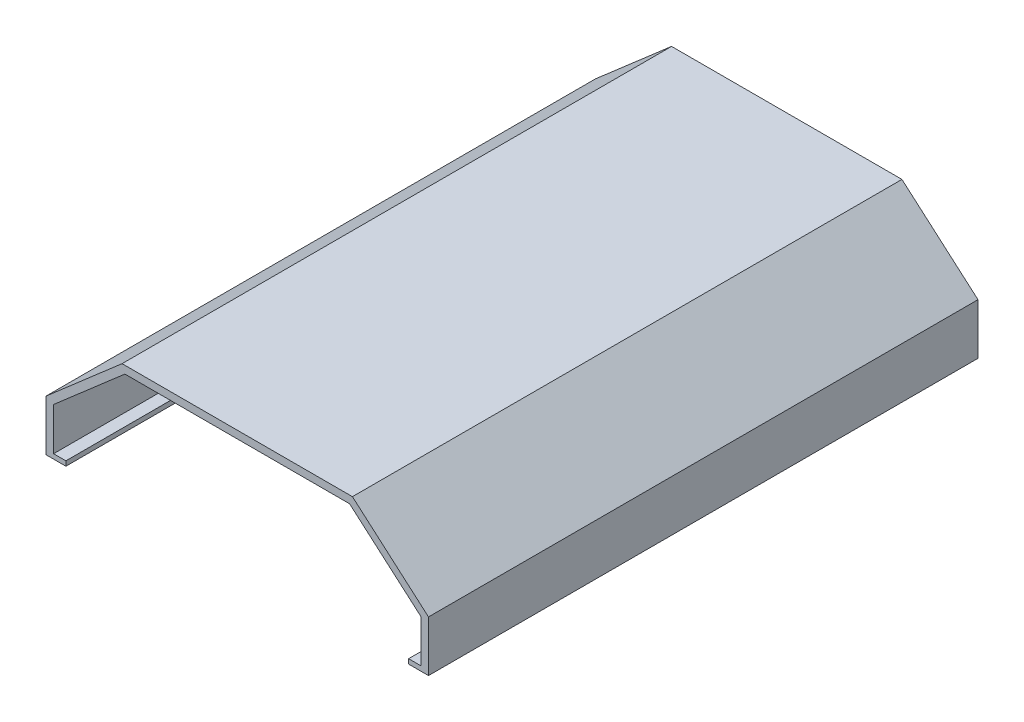
SolidWorks part; units mm, degrees
ref_plane "Front Plane" through (0, 0, 0) normal (0, 0, 1) x (1, 0, 0)
ref_plane "Top Plane" through (0, 0, 0) normal (0, 1, 0) x (1, 0, 0)
ref_plane "Right Plane" through (0, 0, 0) normal (1, 0, 0) x (0, 0, -1)
sketch "Sketch1" plane through (0, 0, 0) normal (0, 0, 1) x (1, 0, 0)
  line L0 (2.1, 1.3) -> (5.5, 1.3)
  line L1 (5.5, 1.3) -> (5.5, 0)
  line L2 (5.5, 0) -> (0, 0)
  line L4 (83.9748, 30.2469) -> (21.8252, 30.2469)
  line L5 (21.8252, 30.2469) -> (2.1, 13.1)
  line L6 (2.1, 13.1) -> (2.1, 1.3)
  line L7 (84.7599, 32.3469) -> (21.0401, 32.3469)
  line L8 (21.0401, 32.3469) -> (0, 14.057)
  line L9 (0, 14.057) -> (0, 0)
  line L10 (105.8, 14.057) -> (105.8, 0)
  line L11 (84.7599, 32.3469) -> (105.8, 14.057)
  line L12 (103.7, 13.1) -> (103.7, 1.3)
  line L13 (83.9748, 30.2469) -> (103.7, 13.1)
  line L14 (100.3, 0) -> (105.8, 0)
  line L15 (100.3, 1.3) -> (100.3, 0)
  line L16 (103.7, 1.3) -> (100.3, 1.3)
  line L17 (5.5, 1.3) -> (100.3, 1.3) construction
  line L18 (52.9, 30.2469) -> (52.9, 32.3469) construction
  point P11 (2.75, 0)
  point P13 (52.9, 1.3)
  dimension "D1" = 1.3
  dimension "D2" = 2.1
  dimension "D3" = 2.1
  dimension "D4" = 2.1
  dimension "D5" = 5.5
  dimension "D6" = 3.4
  dimension "D7" = 63.7199
  dimension "D8" = 62.1496
  dimension "D9" = 94.8
  dimension "D10" = 3.4
  dimension "D11" = 5.5
  dimension "D12" = 1.3
  dimension "D13" = 11.8
  dimension "D14" = 49
  dimension "D15" = 2.1
extrude "Boss-Extrude1" add sketch "Sketch1" along normal blind 145
sketch "Sketch2" plane through (0, 0, 0) normal (0, 0, -1) x (-1, 0, 0)
  line L0 (0, 0) -> (-5.5, 0) construction
  line L1 (-2.1, 0) -> (0, 0)
  line L2 (-100.3, 0) -> (-105.8, 0) construction
  line L3 (-105.8, 0) -> (-103.7, 0)
  line L16 (-2.1, 13.1) -> (-2.1, 1.3)
  line L17 (-2.1, 1.3) -> (-5.5, 1.3)
  line L18 (-5.5, 1.3) -> (-5.5, 0)
  line L19 (-5.5, 0) -> (0, 0)
  line L20 (0, 0) -> (0, 14.057)
  line L21 (0, 14.057) -> (-21.0401, 32.3469)
  line L22 (-21.0401, 32.3469) -> (-84.7599, 32.3469)
  line L23 (-84.7599, 32.3469) -> (-105.8, 14.057)
  line L24 (-105.8, 14.057) -> (-105.8, 0)
  line L25 (-105.8, 0) -> (-100.3, 0)
  line L26 (-100.3, 0) -> (-100.3, 1.3)
  line L27 (-100.3, 1.3) -> (-103.7, 1.3)
  line L28 (-103.7, 1.3) -> (-103.7, 13.1)
  line L29 (-103.7, 13.1) -> (-83.9748, 30.2469)
  line L30 (-83.9748, 30.2469) -> (-21.8252, 30.2469)
  line L31 (-21.8252, 30.2469) -> (-2.1, 13.1)
  line L32 (-2.1, 13.1) -> (-2.1, 0)
  line L36 (0, 0) -> (0, 14.057)
  line L37 (0, 14.057) -> (-21.0401, 32.3469)
  line L38 (-21.0401, 32.3469) -> (-84.7599, 32.3469)
  line L39 (-84.7599, 32.3469) -> (-105.8, 14.057)
  line L40 (-105.8, 14.057) -> (-105.8, 0)
  line L44 (-103.7, 0) -> (-103.7, 13.1)
  line L45 (-103.7, 13.1) -> (-83.9748, 30.2469)
  line L46 (-83.9748, 30.2469) -> (-21.8252, 30.2469)
  line L47 (-21.8252, 30.2469) -> (-2.1, 13.1)
  dimension "D1" = 0
extrude "Boss-Extrude2" add sketch "Sketch2" along normal blind 7
